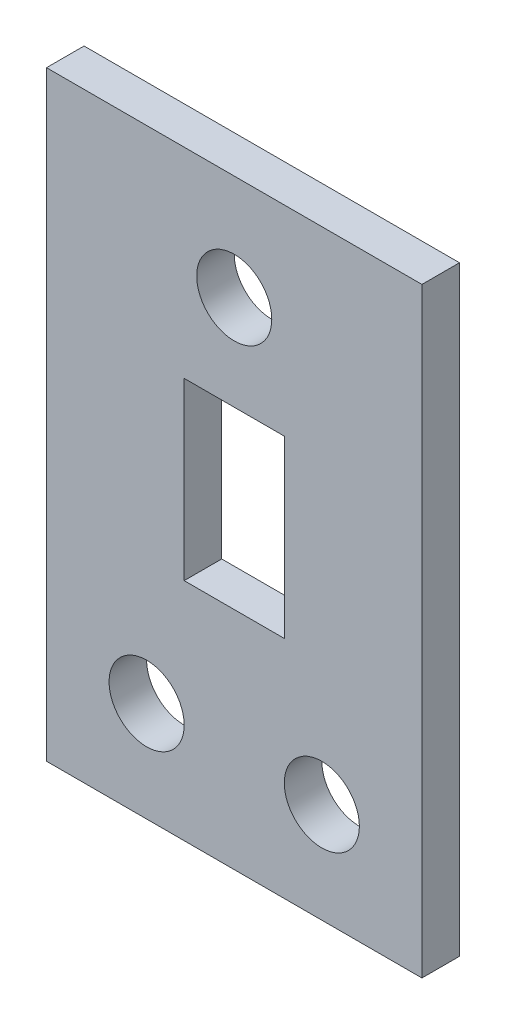
SolidWorks part; units mm, degrees
ref_plane "Plan de face" through (0, 0, 0) normal (0, 0, 1) x (1, 0, 0)
ref_plane "Plan de dessus" through (0, 0, 0) normal (0, 1, 0) x (1, 0, 0)
ref_plane "Plan de droite" through (0, 0, 0) normal (1, 0, 0) x (0, 0, -1)
sketch "Esquisse1" plane through (0, 0, 0) normal (0, 0, 1) x (1, 0, 0)
  line L1 (-12.5455, 32.9532) -> (2.4545, 32.9532)
  line L2 (-12.5455, 32.9532) -> (-12.5455, 8.9532)
  line L3 (-12.5455, 8.9532) -> (2.4545, 8.9532)
  line L4 (2.4545, 32.9532) -> (2.4545, 8.9532)
  dimension "D1" = 15
  dimension "D2" = 24
extrude "Extrusion1" add sketch "Esquisse1" along normal blind 1.5
sketch "Esquisse2" plane through (0, 0, 1.5) normal (0, 0, 1) x (1, 0, 0)
  line L0 (-12.5455, 8.9532) -> (2.4545, 8.9532) construction
  line L1 (-12.5455, 32.9532) -> (-12.5455, 8.9532) construction
  line L2 (2.4545, 8.9532) -> (2.4545, 32.9532) construction
  line L3 (2.4545, 8.9532) -> (2.4545, 32.9532) construction
  line L5 (-7.0455, 24.9532) -> (-3.0455, 24.9532)
  line L6 (-7.0455, 24.9532) -> (-7.0455, 17.9532)
  line L7 (-7.0455, 17.9532) -> (-3.0455, 17.9532)
  line L8 (-3.0455, 24.9532) -> (-3.0455, 17.9532)
  circle A0 centre (-8.5455, 12.9532) radius 1.5
  circle A1 centre (-1.5455, 12.9532) radius 1.5
  circle A2 centre (-5.0455, 28.7474) radius 1.5
  dimension "D1" = 4
  dimension "D5" = 7
  dimension "D2" = 4
  dimension "D3" = 4
  dimension "D4" = 4
  dimension "D6" = 4
  dimension "D7" = 5
  dimension "D8" = 5.5
extrude "Extrusion2" cut sketch "Esquisse2" against normal blind 2
